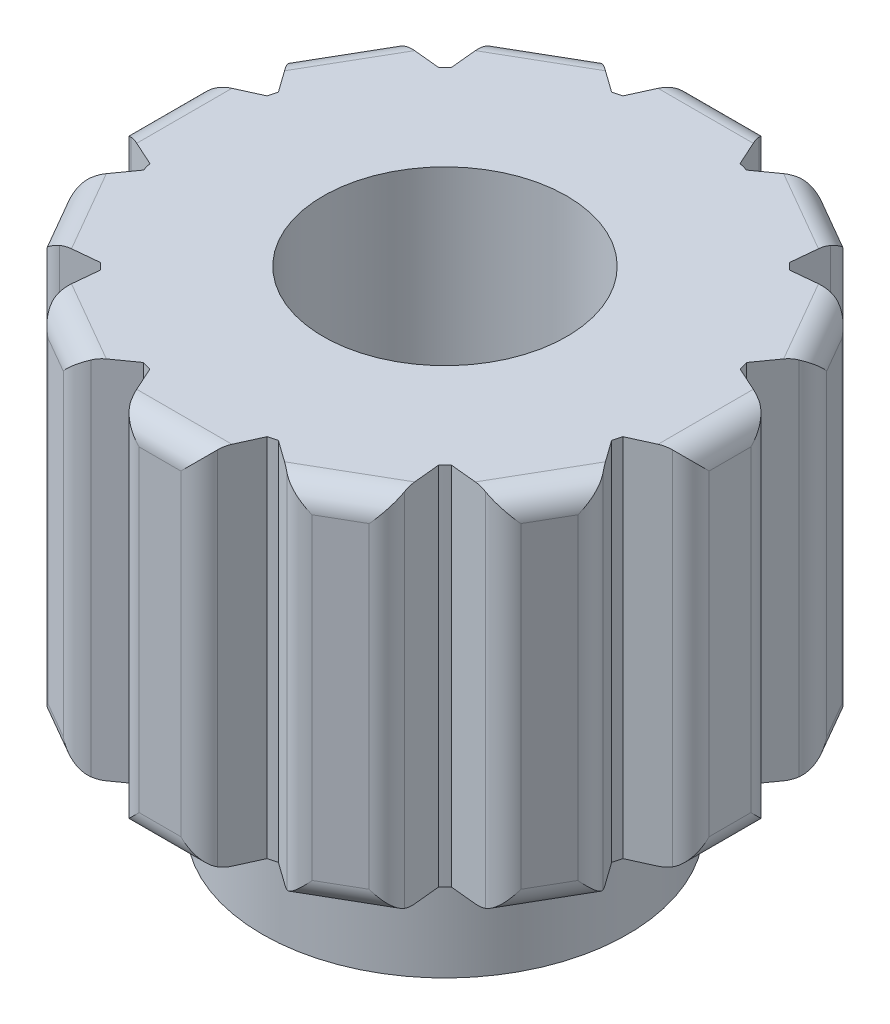
SolidWorks part; units mm, degrees
ref_plane "Front Plane" through (0, 0, 0) normal (0, 0, 1) x (1, 0, 0)
ref_plane "Top Plane" through (0, 0, 0) normal (0, 1, 0) x (1, 0, 0)
ref_plane "Right Plane" through (0, 0, 0) normal (1, 0, 0) x (0, 0, -1)
sketch "Sketch1" plane through (0, 0, 0) normal (0, 1, 0) x (1, 0, 0)
  circle A0 centre (0, 0) radius 12.7
  dimension "D1" = 25.4
extrude "Boss-Extrude1" add sketch "Sketch1" along normal blind 19.05 contours A0
sketch "Sketch2" plane through (0, 19.05, 0) normal (0, 1, 0) x (1, 0, 0)
  line L0 (0, -14.859) -> (0, 19.6109) construction
  line L1 (-1.905, 14.859) -> (1.905, 14.859)
  line L2 (1.905, 14.859) -> (3.3684, 11.6398)
  line L3 (3.3684, 11.6398) -> (-3.3684, 11.6398)
  line L4 (-1.905, 14.859) -> (-3.3684, 11.6398)
  circle A0 centre (0, 0) radius 14.859 construction
  point P10 (0, 11.6398)
  point P11 (0, 14.859)
  dimension "D1" = 29.718
  dimension "D2" = 3.81
extrude "Boss-Extrude2" add sketch "Sketch2" against normal blind 19.05
pattern_circular "CirPattern1" count 12 over 360 about axis through (0, 0, 0) along (0, 1, 0) of "Boss-Extrude2"
fillet "Fillet1" radius 1.27 48 edges at (5.7797, 9.525, -13.8208) (7.4295, 0, -12.8683) (9.0793, 9.525, -11.9158) (7.4295, 19.05, -12.8683) (11.9158, 9.525, -9.0793) (12.8683, 0, -7.4295) (13.8208, 9.525, -5.7797) (12.8683, 19.05, -7.4295) (14.859, 9.525, -1.905) (14.859, 0, 0) (14.859, 9.525, 1.905) (14.859, 19.05, 0) (13.8208, 9.525, 5.7797) (12.8683, 0, 7.4295) (11.9158, 9.525, 9.0793) (12.8683, 19.05, 7.4295) (9.0793, 9.525, 11.9158) (7.4295, 0, 12.8683) (5.7797, 9.525, 13.8208) (7.4295, 19.05, 12.8683) (1.905, 9.525, 14.859) (0, 0, 14.859) (-1.905, 9.525, 14.859) (0, 19.05, 14.859) (-5.7797, 9.525, 13.8208) (-7.4295, 0, 12.8683) (-9.0793, 9.525, 11.9158) (-7.4295, 19.05, 12.8683) (-11.9158, 9.525, 9.0793) (-12.8683, 0, 7.4295) (-13.8208, 9.525, 5.7797) (-12.8683, 19.05, 7.4295) (-14.859, 9.525, 1.905) (-14.859, 0, 0) (-14.859, 9.525, -1.905) (-14.859, 19.05, 0) (-13.8208, 9.525, -5.7797) (-12.8683, 0, -7.4295) (-11.9158, 9.525, -9.0793) (-12.8683, 19.05, -7.4295) (-9.0793, 9.525, -11.9158) (-7.4295, 0, -12.8683) (-5.7797, 9.525, -13.8208) (-7.4295, 19.05, -12.8683) (-1.905, 9.525, -14.859) (0, 19.05, -14.859) (0, 0, -14.859) (1.905, 9.525, -14.859)
sketch "Sketch3" plane through (0, 0, 0) normal (0, -1, 0) x (1, 0, 0)
  circle A0 centre (0, 0) radius 9.525
  dimension "D1" = 19.05
extrude "Boss-Extrude3" add sketch "Sketch3" along normal blind 6.35
sketch "Sketch4" plane through (0, -6.35, 0) normal (0, -1, 0) x (1, 0, 0)
  circle A0 centre (0, 0) radius 6.35
  dimension "D1" = 12.7
extrude "Cut-Extrude1" cut sketch "Sketch4" against normal through all
